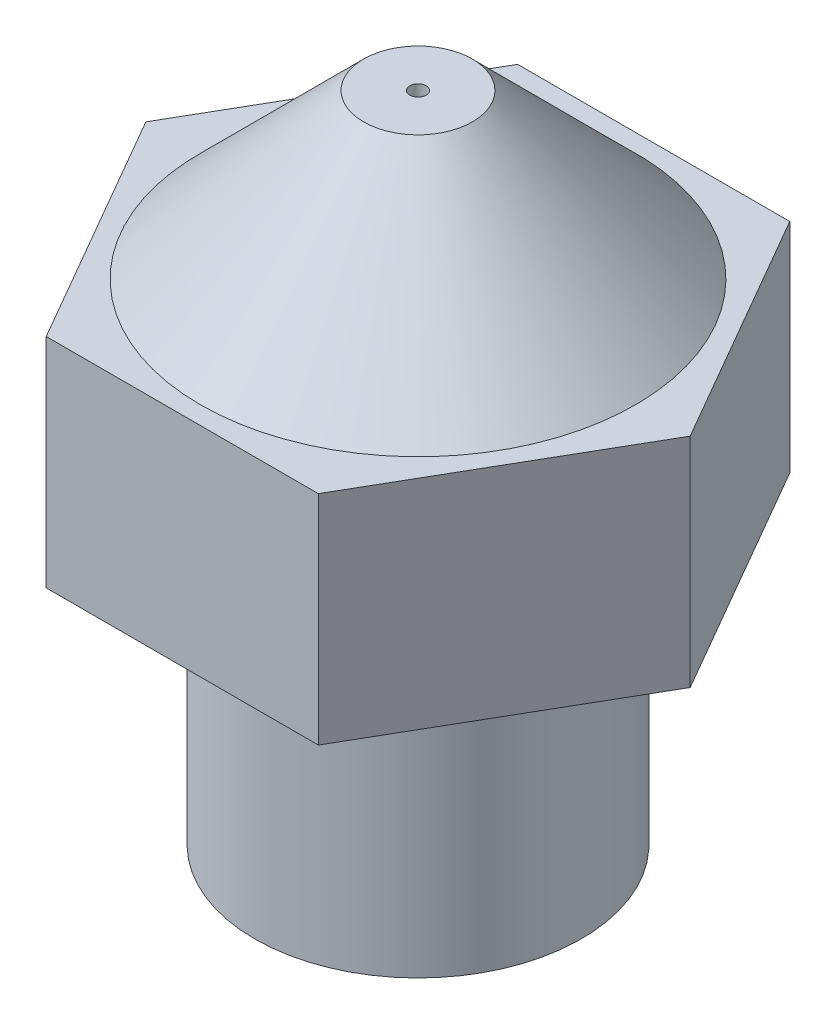
SolidWorks part; units mm, degrees
ref_plane "Front Plane" through (0, 0, 0) normal (0, 0, 1) x (1, 0, 0)
ref_plane "Top Plane" through (0, 0, 0) normal (0, 1, 0) x (1, 0, 0)
ref_plane "Right Plane" through (0, 0, 0) normal (1, 0, 0) x (0, 0, -1)
sketch "Sketch1" plane through (0, 0, 0) normal (0, 1, 0) x (1, 0, 0)
  circle A0 centre (0, 0) radius 3
  dimension "D1" = 6
extrude "Boss-Extrude1" add sketch "Sketch1" along normal blind 5
sketch "Sketch2" plane through (0, 5, 0) normal (0, 1, 0) x (1, 0, 0)
  line L1 (5, 0) -> (2.5, 4.3301)
  line L2 (2.5, 4.3301) -> (-2.5, 4.3301)
  line L3 (-2.5, 4.3301) -> (-5, 0)
  line L4 (-5, 0) -> (-2.5, -4.3301)
  line L5 (-2.5, -4.3301) -> (2.5, -4.3301)
  line L6 (2.5, -4.3301) -> (5, 0)
  circle A0 centre (0, 0) radius 4.3301 construction
  dimension "D1" = 5
extrude "Boss-Extrude2" add sketch "Sketch2" along normal blind 4
sketch "Sketch4" plane through (0, 9, 0) normal (0, 1, 0) x (1, 0, 0)
  circle A0 centre (0, 0) radius 1
  dimension "D1" = 2
extrude "Boss-Extrude4" add sketch "Sketch4" along normal blind 3
draft "Draft4" type of draft neutral plane draft angle 45 faces to draft 1 face at (0, 12, 1) neutral plane through (0, 12, 0) neutral plane normal (0, 1, 0) parameters "D1"=45
sketch "Sketch5" plane through (0, 12, 0) normal (0, 1, 0) x (1, 0, 0)
  circle A0 centre (0, 0) radius 0.15
  dimension "D1" = 0.3
extrude "Cut-Extrude1" cut sketch "Sketch5" against normal blind 50
sketch "Sketch6" plane through (0, 0, 0) normal (0, -1, 0) x (1, 0, 0)
  circle A0 centre (0, 0) radius 1.5
  dimension "D1" = 3
extrude "Cut-Extrude2" cut sketch "Sketch6" against normal blind 5
